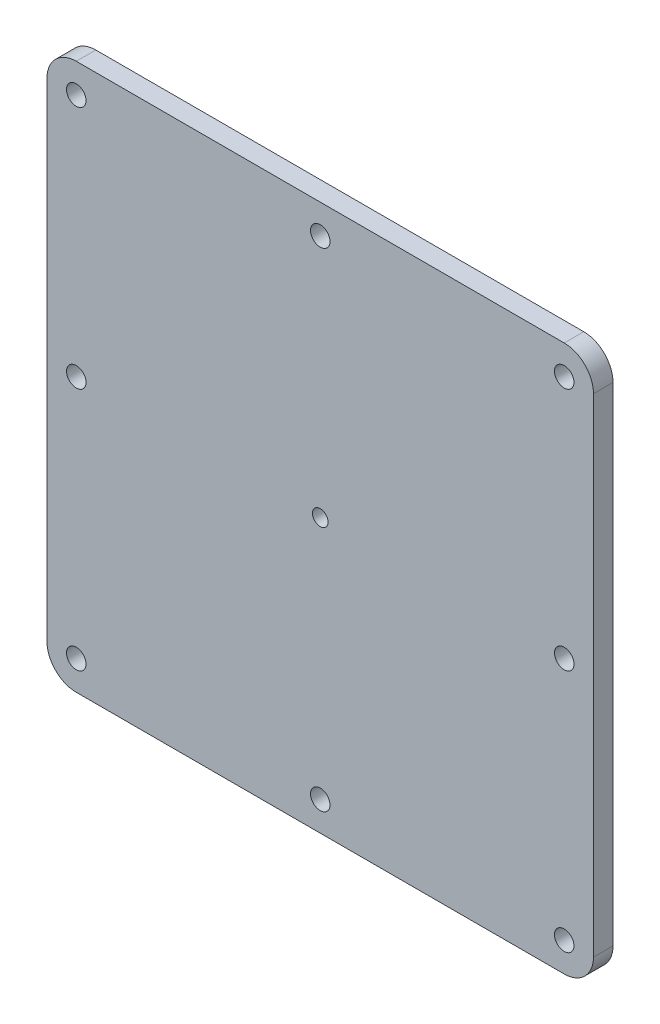
SolidWorks part; units mm, degrees
ref_plane "Front Plane" through (0, 0, 0) normal (0, 0, 1) x (1, 0, 0)
ref_plane "Top Plane" through (0, 0, 0) normal (0, 1, 0) x (1, 0, 0)
ref_plane "Right Plane" through (0, 0, 0) normal (1, 0, 0) x (0, 0, -1)
sketch "Sketch2" plane through (0, 0, 0) normal (0, 0, 1) x (1, 0, 0)
  line L0 (-125, 125) -> (125, 125) construction
  line L1 (-125, 140) -> (125, 140)
  line L2 (-140, 125) -> (-140, -125)
  line L3 (-125, -140) -> (125, -140)
  line L4 (140, 125) -> (140, -125)
  line L5 (-140, 140) -> (140, -140) construction
  line L6 (-140, -140) -> (140, 140) construction
  line L7 (125, 125) -> (125, -125) construction
  line L8 (125, -125) -> (-125, -125) construction
  line L9 (-125, -125) -> (-125, 125) construction
  arc A0 (-140, -125) -> (-125, -140) centre (-125, -125) ccw
  arc A1 (125, -140) -> (140, -125) centre (125, -125) ccw
  arc A2 (125, 140) -> (140, 125) centre (125, 125) cw
  arc A3 (-125, 140) -> (-140, 125) centre (-125, 125) ccw
  circle A4 centre (-125, 125) radius 5
  circle A5 centre (0, 125) radius 5
  circle A6 centre (125, 125) radius 5
  circle A13 centre (0, 0) radius 4
  circle A14 centre (125, 0) radius 5
  circle A15 centre (-125, 0) radius 5
  circle A16 centre (-125, -125) radius 5
  circle A17 centre (0, -125) radius 5
  circle A18 centre (125, -125) radius 5
  point P0 (0, 0)
  dimension "D3" = 15
  dimension "D4" = 10
  dimension "D5" = 10
  dimension "D6" = 10
  dimension "D7" = 8
  dimension "D8" = 10
  dimension "D9" = 10
  dimension "D10" = 10
  dimension "D11" = 10
  dimension "D1" = 280
  dimension "D2" = 280
extrude "Boss-Extrude1" add sketch "Sketch2" along normal blind 10
